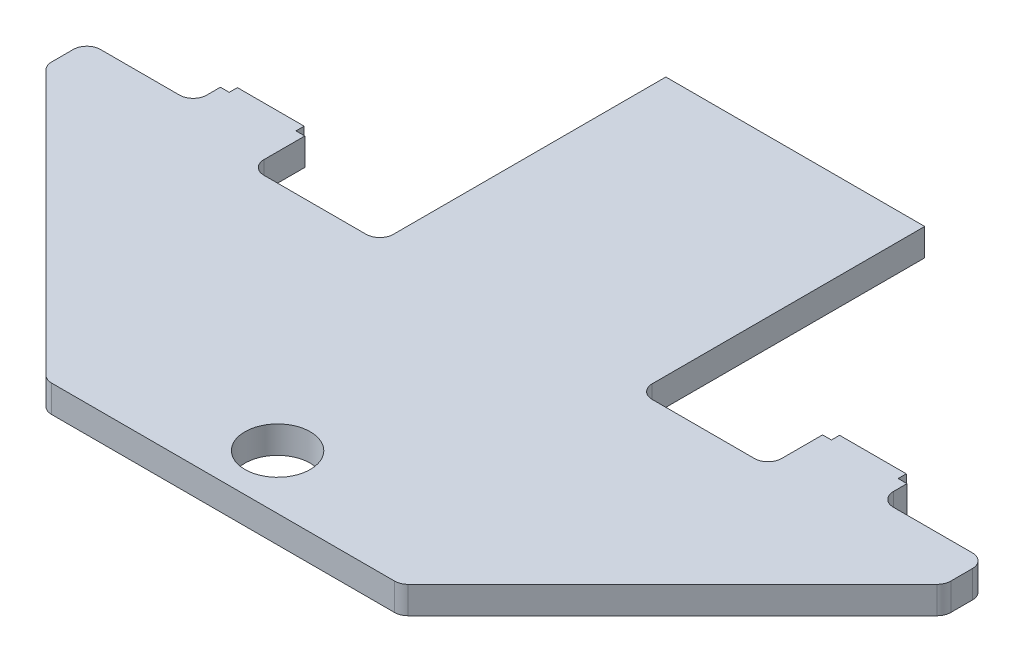
SolidWorks part; units mm, degrees
material "Film PE haute densité"
ref_plane "Plan de face" through (0, 0, 0) normal (0, 0, 1) x (1, 0, 0)
ref_plane "Plan de dessus" through (0, 0, 0) normal (0, 1, 0) x (1, 0, 0)
ref_plane "Plan de droite" through (0, 0, 0) normal (1, 0, 0) x (0, 0, -1)
sketch "Sketch1" plane through (0, 0, 0) normal (0, 1, 0) x (1, 0, 0)
  line L0 (-165, -30) -> (-165, -45)
  line L1 (-165, -45) -> (-65, -145)
  line L2 (-65, -145) -> (65, -145)
  line L3 (-165, -30) -> (-126, -30)
  line L4 (-126, -30) -> (-126, -20)
  line L5 (-126, -20) -> (-122.75, -20)
  line L6 (-122.75, -20) -> (-122.75, -17)
  line L7 (-122.75, -17) -> (-98.25, -17)
  line L8 (-98.25, -17) -> (-98.25, -20)
  line L9 (-98.25, -20) -> (-95, -20)
  line L10 (-95, -20) -> (-95, -40)
  line L11 (-95, -40) -> (-47.5, -40)
  line L12 (-47.5, -40) -> (-47.5, 123.3333)
  line L13 (-15, 145) -> (15, 145)
  line L14 (0, 145) -> (0, -145) construction
  line L15 (47.5, -40) -> (47.5, 123.3333)
  line L16 (95, -40) -> (47.5, -40)
  line L17 (95, -20) -> (95, -40)
  line L18 (98.25, -20) -> (95, -20)
  line L19 (98.25, -17) -> (98.25, -20)
  line L20 (122.75, -17) -> (98.25, -17)
  line L21 (122.75, -20) -> (122.75, -17)
  line L22 (126, -20) -> (122.75, -20)
  line L23 (126, -30) -> (126, -20)
  line L24 (165, -30) -> (126, -30)
  line L25 (165, -45) -> (65, -145)
  line L26 (165, -30) -> (165, -45)
  line L27 (-47.5, 123.3333) -> (-15, 145)
  line L28 (47.5, 123.3333) -> (15, 145)
  line L29 (-47.5, 123.3333) -> (-165, 45) construction
  circle A0 centre (0, 113) radius 12
  circle A1 centre (0, -125) radius 12
  dimension "D17" = 24
  dimension "D18" = 32
  dimension "D19" = 20
  dimension "D1" = 31
  dimension "D2" = 24.5
  dimension "D3" = 3
  dimension "D4" = 145
  dimension "D5" = 130
  dimension "D6" = 330
  dimension "D7" = 45
  dimension "D8" = 20
  dimension "D9" = 221
  dimension "D10" = 40
  dimension "D11" = 30
  dimension "D12" = 30
  dimension "D13" = 45
  dimension "D14" = 100
  dimension "D15" = 95
  dimension "D16" = 290
extrude "Extrude1" add sketch "Sketch1" along normal blind 10
fillet "Fillet1" radius 5 16 edges at (-126, 5, 30) (165, 5, 30) (126, 5, 30) (95, 5, 40) (47.5, 5, 40) (-165, 5, 30) (-95, 5, 40) (-47.5, 5, 40) (-47.5, 5, -123.3333) (-15, 5, -145) (15, 5, -145) (47.5, 5, -123.3333) (165, 5, 45) (65, 5, 145) (-65, 5, 145) (-165, 5, 45)
sketch "Esquisse1" plane through (0, 10, 0) normal (0, 1, 0) x (1, 0, 0)
  line L0 (-47.5, 120.6574) -> (-47.5, -35) construction
  line L1 (-47.5, 145) -> (47.5, 145)
  line L2 (-47.5, 145) -> (-47.5, 65)
  line L3 (-47.5, 65) -> (47.5, 65)
  line L4 (47.5, 145) -> (47.5, 65)
  line L5 (47.5, -35) -> (47.5, 120.6574) construction
  line L6 (13.4861, 145) -> (-13.4861, 145) construction
  dimension "D1" = 65
extrude "Enlèv. mat.-Extru.1" cut sketch "Esquisse1" against normal through all
